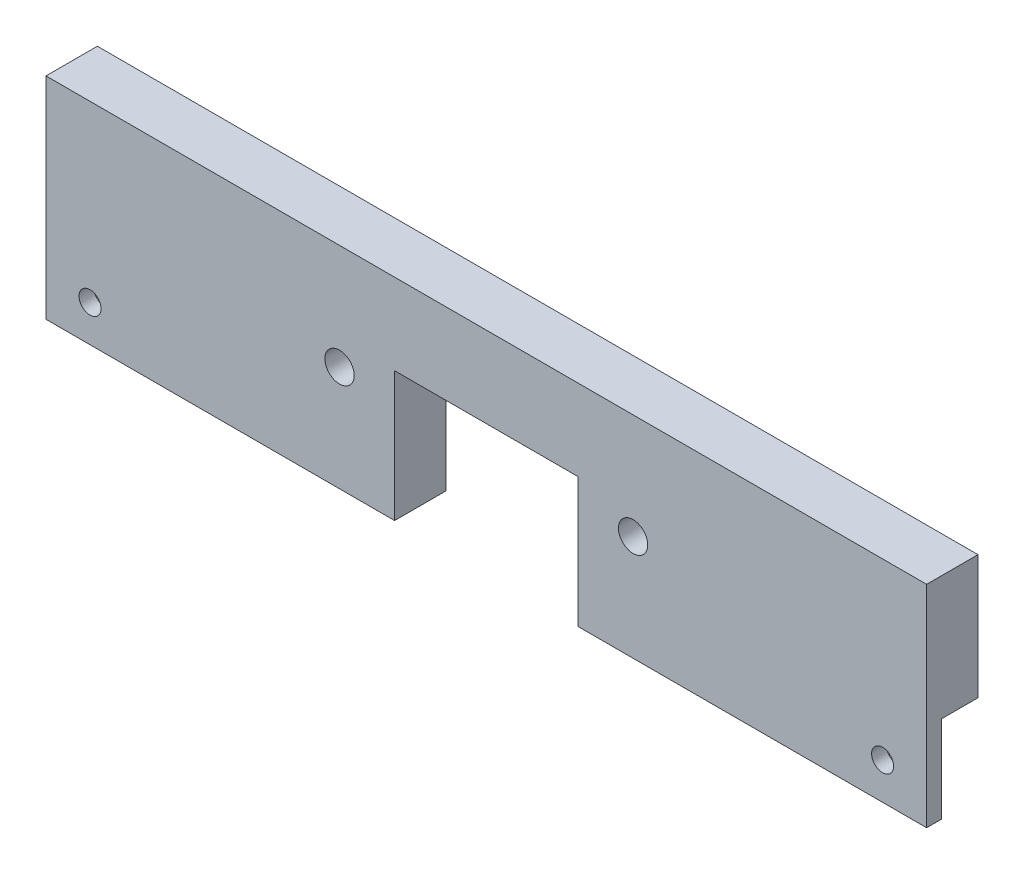
SolidWorks part; units mm, degrees
ref_plane "Front Plane" through (0, 0, 0) normal (0, 0, 1) x (1, 0, 0)
ref_plane "Top Plane" through (0, 0, 0) normal (0, 1, 0) x (1, 0, 0)
ref_plane "Right Plane" through (0, 0, 0) normal (1, 0, 0) x (0, 0, -1)
sketch "Sketch1" plane through (0, 0, 0) normal (0, 0, 1) x (1, 0, 0)
  line L0 (-54, 57.6028) -> (-54, 17.3336) construction
  line L1 (-60, -40) -> (60, -40) construction
  line L2 (-60, -40) -> (-60, 40) construction
  line L3 (-60, 40) -> (60, 40) construction
  line L4 (60, -40) -> (60, 40) construction
  line L5 (-60, -40) -> (60, 40) construction
  line L6 (-60, 40) -> (60, -40) construction
  line L7 (0, 0) -> (0, 20.6641) construction
  line L8 (48, 23.11) -> (48, 9.16)
  line L9 (-60, 23.11) -> (-48, 23.11)
  line L10 (-60, 23.11) -> (-60, 9.16)
  line L11 (-60, 9.16) -> (-48, 9.16)
  line L12 (-48, 23.11) -> (-48, 9.16)
  line L13 (60, 9.16) -> (48, 9.16)
  line L14 (60, 23.11) -> (60, 9.16)
  line L15 (60, 23.11) -> (48, 23.11)
  circle A0 centre (-54, 16.27) radius 1.5 construction
  circle A1 centre (-54, -16.28) radius 1.5 construction
  circle A2 centre (54, -16.28) radius 1.5 construction
  circle A3 centre (54, 16.27) radius 1.5 construction
  point P0 (0, 0)
  dimension "D3" = 23.73
  dimension "D5" = 32.55
  dimension "D6" = 3
  dimension "D7" = 3
  dimension "D1" = 120
  dimension "D2" = 6
  dimension "D4" = 80
  dimension "D8" = 12
  dimension "D9" = 6.84
  dimension "D10" = 7.11
sketch "Sketch2" plane through (0, 0, 0) normal (0, 0, 1) x (1, 0, 0)
  line L0 (-60, -40) -> (-60, 40) construction
  line L1 (-60, 11.27) -> (60, 11.27)
  line L2 (-60, 11.27) -> (-60, 40)
  line L3 (-60, 40) -> (60, 40)
  line L4 (60, 11.27) -> (60, 40)
  line L5 (-60, 25.635) -> (60, 25.635) construction
  line L6 (0, 1.5207) -> (0, 49.7493) construction
  circle A0 centre (-54, 16.27) radius 1.5 construction
  circle A1 centre (-54, 16.27) radius 1.5
  circle A2 centre (54, 16.27) radius 1.5
  circle A3 centre (-20, 25.635) radius 2
  circle A4 centre (20, 25.635) radius 2
  point P21 (0, 25.635)
  dimension "D2" = 3
  dimension "D3" = 3
  dimension "D4" = 4
  dimension "D5" = 20
  dimension "D1" = 5
extrude "Boss-Extrude1" add sketch "Sketch2" along normal blind 7
sketch "Sketch3" plane through (0, 0, 0) normal (0, 0, -1) x (-1, 0, 0)
  line L1 (-60, 23.11) -> (-48, 23.11)
  line L2 (-60, 23.11) -> (-60, 9.16)
  line L3 (-60, 9.16) -> (-48, 9.16)
  line L4 (-48, 23.11) -> (-48, 9.16)
  line L5 (60, 23.11) -> (48, 23.11)
  line L6 (60, 23.11) -> (60, 9.16)
  line L7 (60, 9.16) -> (48, 9.16)
  line L8 (48, 23.11) -> (48, 9.16)
extrude "Cut-Extrude1" cut sketch "Sketch3" against normal blind 5
sketch "Sketch4" plane through (0, 0, 7) normal (0, 0, 1) x (1, 0, 0)
  line L0 (0, 0) -> (0, 53.2081) construction
  line L1 (-60, 40) -> (60, -40) construction
  line L3 (-12.5, -17.7863) -> (12.5, -17.7863)
  line L4 (-12.5, -17.7863) -> (-12.5, 28.9607)
  line L5 (-12.5, 28.9607) -> (12.5, 28.9607)
  line L6 (12.5, -17.7863) -> (12.5, 28.9607)
  line L7 (-12.5, -17.7863) -> (12.5, 28.9607) construction
  line L8 (-12.5, 28.9607) -> (12.5, -17.7863) construction
  point P4 (0, 5.5872)
  dimension "D1" = 25
extrude "Cut-Extrude2" cut sketch "Sketch4" against normal up to surface (7 mm away) up to face at (0, 24.3725, 0)
sketch "Sketch5" plane through (0, 0, 0) normal (0, 0, 1) x (1, 0, 0)
  circle A0 centre (20, 25.635) radius 4
  circle A1 centre (-20, 25.635) radius 4
  dimension "D1" = 8
  dimension "D2" = 8
extrude "Cut-Extrude3" cut sketch "Sketch5" along normal blind 2
